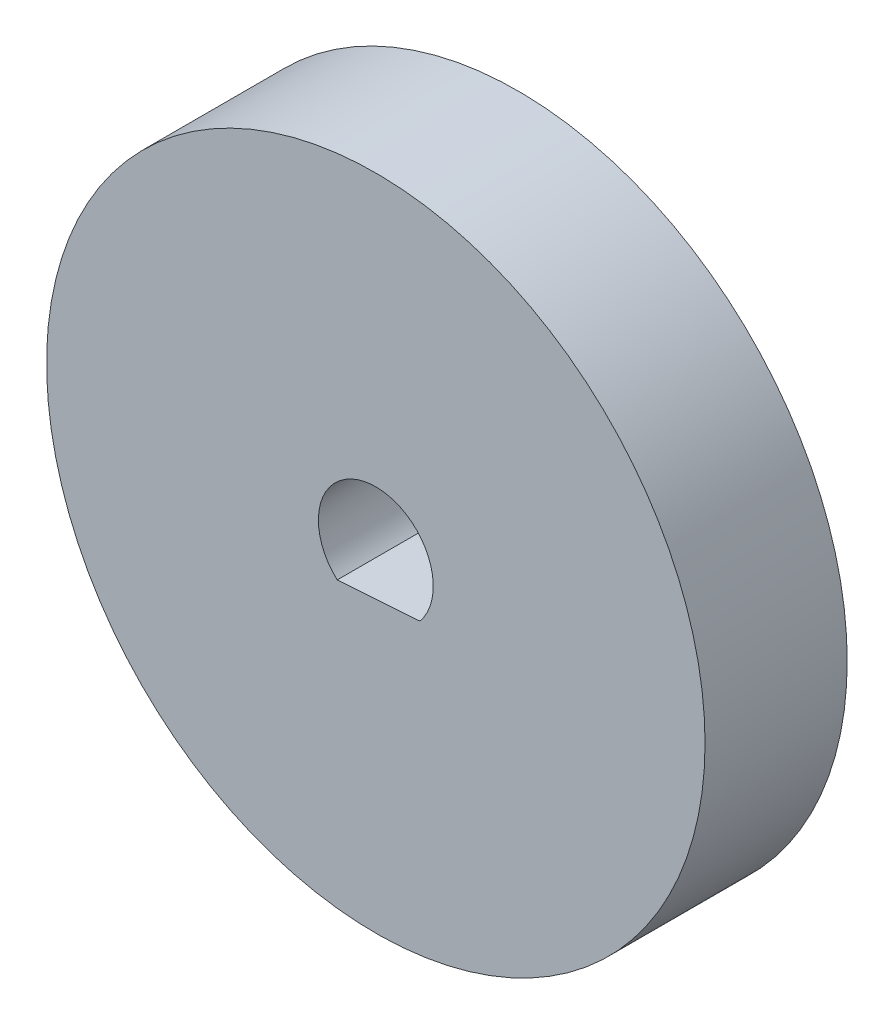
SolidWorks part; units mm, degrees
ref_plane "Front Plane" through (0, 0, 0) normal (0, 0, 1) x (1, 0, 0)
ref_plane "Top Plane" through (0, 0, 0) normal (0, 1, 0) x (1, 0, 0)
ref_plane "Right Plane" through (0, 0, 0) normal (1, 0, 0) x (0, 0, -1)
sketch "Sketch1" plane through (0, 0, 0) normal (0, 0, 1) x (1, 0, 0)
  circle A0 centre (0, 7.2896) radius 11.176
  dimension "D1" = 22.352
extrude "Boss-Extrude1" add sketch "Sketch1" along normal blind 4.826
sketch "Sketch2" plane through (0, 0, 0) normal (0, 0, -1) x (-1, 0, 0)
  line L1 (-1.4968, 6.0398) -> (1.3108, 5.8459)
  circle A0 centre (0, 7.2896) radius 1.95
  circle A1 centre (0, 7.2896) radius 11.176 construction
  dimension "D1" = 3.9
  dimension "D3" = 0
  dimension "D2" = 1.35
extrude "Cut-Extrude1" cut sketch "Sketch2" against normal through all contours L1 A0
equation "\"MDF\"= 0.19in"
equation "\"Foamcore\"= .13in"
equation "\"Gmaterial\"= \"MDF\""
equation "\"D1@Boss-Extrude1\"=\"MDF\""
equation "\"PVCID\" = 2.067in"
equation "\"PVCOD\" = 2.375in"
equation "\"GenDiameter\"= 60mm"
equation "\"GenCutDiameter\" = 1.8in"
equation "\"GenCutDistance\" = 1"
equation "\"TowerHeight\" = 6in"
equation "\"TowerFrontBase\" = 3in"
equation "\"FunnelHeight\" = 1in"
equation "\"FunnelAngle\" = 20"
equation "\"TowerSideBase\" = 3in"
equation "\"TowerPanelLength\" = 2in"
equation "\"TowerPanelLeeway\" = 0.5in"
equation "\"BaseLength\" = 10in"
equation "\"BaseWidth\" = 10.5in"
equation "\"WheelHoleLength\" = 3.25in"
equation "\"WheelHoleWidth\" = 26mm"
equation "\"WheelHoleFromBack\" = 1in"
equation "\"DropLength\" = 1in"
equation "\"DropWidth\" = 8.5in"
equation "\"BumperWidth\" = 1in"
equation "\"HoleDiameter\" = 0.25in"
equation "\"SmallHexDiameter\" = 0.185in"
equation "\"SmallHexHeight\" = 0.701in"
equation "\"ScrewSize\" = 0.106in"
equation "\"BigHexDiameter\" = 0.251in"
equation "\"BigHexHeight\" = 0.374in"
equation "\"PCBThickness\" = 0.066in"
equation "\"ConnectorHeight\" = 0.517in"
equation "\"BoardHeight\" = 0.583in"
equation "\"UnoStackHeight\" = 1.351in"
equation "\"UnoStackWidth\" = 3.053in"
equation "\"UnoStackLength\" = 3.152in"
equation "\"HBridgeWidth\" = 1.797in"
equation "\"HBridgeLength\" = 2.236in"
equation "\"DSWidth\" = 1.820in"
equation "\"DSLength\" = 1.833in"
equation "\"StepperWidth\" = 1.799in"
equation "\"StepperLength\" = 2.248in"
equation "\"ULNWidth\" = 1.304in"
equation "\"ULNLength\" = 1.545in"
equation "\"VSwitchHeight\" = 0.392in"
equation "\"VSwitchWidth\" = 0.637in"
equation "\"VSwitchLength\" = 1.097in"
equation "\"SkateWheelDiameter\" = 80mm"
equation "\"SkateWheelThickness\" = 24mm"
equation "\"BaseDistance\" = 3in"
